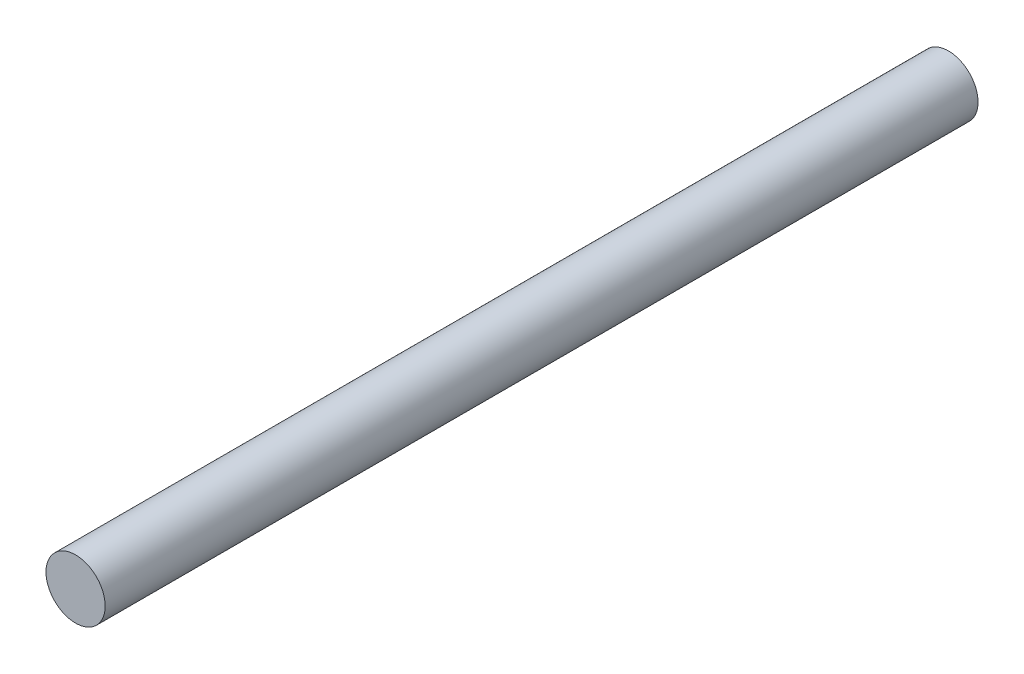
SolidWorks part; units mm, degrees
ref_plane "Plane1" through (0, 0, 0) normal (0, 0, 1) x (1, 0, 0)
ref_plane "Plane2" through (0, 0, 0) normal (0, 1, 0) x (1, 0, 0)
ref_plane "Plane3" through (0, 0, 0) normal (1, 0, 0) x (0, 0, -1)
sketch "Sketch1" plane through (0, 0, 0) normal (0, 0, 1) x (1, 0, 0)
  circle A0 centre (-25.2693, 4.1565) radius 2
  point P1 (-25.2693, 4.1565)
extrude "Boss-Extrude1" add sketch "Sketch1" along normal blind 59
